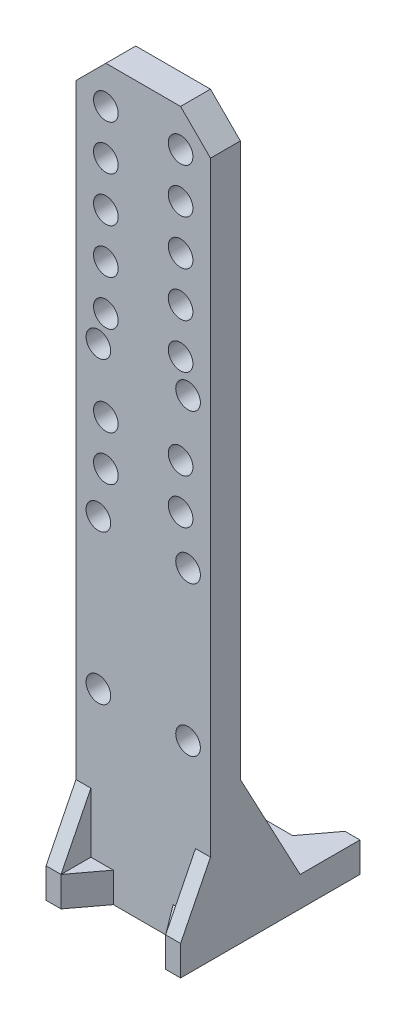
SolidWorks part; units mm, degrees
ref_plane "前视基准面" through (0, 0, 0) normal (0, 0, 1) x (1, 0, 0)
ref_plane "上视基准面" through (0, 0, 0) normal (0, 1, 0) x (1, 0, 0)
ref_plane "右视基准面" through (0, 0, 0) normal (1, 0, 0) x (0, 0, -1)
sketch "草图1" plane through (0, 0, 0) normal (0, 1, 0) x (1, 0, 0)
  line L1 (-9, 8) -> (9, 8)
  line L2 (-9, 8) -> (-9, -8)
  line L3 (-9, -8) -> (9, -8)
  line L4 (9, 8) -> (9, -8)
  line L5 (-9, 8) -> (9, -8) construction
  line L6 (-9, -8) -> (9, 8) construction
  point P0 (0, 0)
  dimension "D1" = 16
  dimension "D2" = 18
extrude "凸台-拉伸1" add sketch "草图1" along normal blind 4
sketch "草图2" plane through (0, 4, 0) normal (0, 1, 0) x (1, 0, 0)
  circle A0 centre (0, 0) radius 1.65
  dimension "D1" = 3.3
extrude "切除-拉伸1" cut sketch "草图2" against normal blind 4
sketch "草图3" plane through (0, 4, 0) normal (0, 1, 0) x (1, 0, 0)
  line L0 (-9, 0) -> (9, 0) construction
  line L1 (-9, 8) -> (-9, -8) construction
  line L2 (9, -8) -> (9, 8) construction
  line L3 (0, 8) -> (0, -8) construction
  line L4 (9, 8) -> (-9, 8) construction
  line L5 (-9, -8) -> (9, -8) construction
  line L6 (-9, -8) -> (-9, -12)
  line L7 (-9, -12) -> (-7, -12)
  line L8 (-7, -12) -> (-4, -8)
  line L9 (-4, -8) -> (-9, -8)
  line L10 (7, -12) -> (4, -8)
  line L11 (9, -12) -> (7, -12)
  line L12 (9, -8) -> (9, -12)
  line L13 (4, -8) -> (9, -8)
  line L14 (9, 12) -> (7, 12)
  line L15 (9, 8) -> (9, 12)
  line L16 (4, 8) -> (9, 8)
  line L17 (7, 12) -> (4, 8)
  line L18 (-7, 12) -> (-4, 8)
  line L19 (-9, 12) -> (-7, 12)
  line L20 (-9, 8) -> (-9, 12)
  line L21 (-4, 8) -> (-9, 8)
  dimension "D1" = 4
  dimension "D2" = 2
  dimension "D3" = 5
extrude "凸台-拉伸2" add sketch "草图3" against normal blind 4
sketch "草图4" plane through (0, 4, 0) normal (0, 1, 0) x (1, 0, 0)
  line L0 (-9, 12) -> (-9, -12) construction
  line L1 (-9, -8) -> (9, -8)
  line L2 (-9, -8) -> (-9, -4)
  line L3 (-9, -4) -> (9, -4)
  line L4 (9, -8) -> (9, -4)
  line L5 (9, -12) -> (9, 12) construction
  dimension "D1" = 4
extrude "凸台-拉伸3" add sketch "草图4" along normal blind 100
sketch "草图5" plane through (9, 0, 0) normal (1, 0, 0) x (0, 0, -1)
  line L0 (-4, 19) -> (-4, 4)
  line L1 (-4, 104) -> (-4, 4) construction
  line L2 (-4, 4) -> (4, 4)
  line L4 (4, 4) -> (-4, 19)
  line L5 (-8, 12) -> (-8, 4)
  line L6 (-8, 104) -> (-8, 4) construction
  line L7 (-8, 4) -> (-12, 4)
  line L8 (-12, 4) -> (-8, 12)
  line L9 (-12, 4) -> (-8, 4) construction
  dimension "D1" = 15
  dimension "D2" = 4
  dimension "D3" = 8
extrude "凸台-拉伸4" add sketch "草图5" against normal blind 2 contours L0 L2 L4 | L8 L5 L7
mirror "镜向1" about plane through (0, 0, 0) normal (1, 0, 0) of "凸台-拉伸4"
sketch "草图6" plane through (0, 0, 4) normal (0, 0, -1) x (-1, 0, 0)
  line L0 (0, 104) -> (0, 4) construction
  line L1 (-9, 104) -> (9, 104) construction
  line L2 (-4, 4) -> (4, 4) construction
  line L3 (-10, 44) -> (10, 44) construction
  line L4 (-9, 104) -> (-9, 19) construction
  line L6 (-7, 19) -> (-9, 19) construction
  circle A0 centre (0, 92) radius 1.65 construction
  circle A1 centre (0, 86) radius 1.65 construction
  circle A2 centre (0, 80) radius 1.65 construction
  circle A3 centre (0, 74) radius 1.65 construction
  circle A4 centre (0, 68) radius 1.65 construction
  circle A5 centre (0, 62) radius 1.65 construction
  circle A6 centre (0, 56) radius 1.65 construction
  circle A7 centre (0, 50) radius 1.65 construction
  circle A8 centre (-6, 44) radius 1.65
  circle A9 centre (6, 44) radius 1.65
  circle A10 centre (6, 64) radius 1.65
  circle A11 centre (-6, 64) radius 1.65
  circle A12 centre (6, 24) radius 1.65
  circle A13 centre (-6, 24) radius 1.65
  circle A14 centre (5, 92) radius 1.65
  circle A15 centre (5, 86) radius 1.65
  circle A16 centre (5, 80) radius 1.65
  circle A17 centre (5, 74) radius 1.65
  circle A18 centre (5, 68) radius 1.65
  circle A20 centre (5, 56) radius 1.65
  circle A21 centre (5, 50) radius 1.65
  circle A22 centre (-5, 50) radius 1.65
  circle A23 centre (-5, 56) radius 1.65
  circle A25 centre (-5, 68) radius 1.65
  circle A26 centre (-5, 74) radius 1.65
  circle A27 centre (-5, 80) radius 1.65
  circle A28 centre (-5, 86) radius 1.65
  circle A29 centre (-5, 92) radius 1.65
  circle A30 centre (5, 62) radius 1.65 [skipped]
  dimension "D2" = 3.3
  dimension "D5" = 3.3
  dimension "D1" = 12
  dimension "D4" = 3
  dimension "D6" = 25
  dimension "D3" = 8
  dimension "D7" = 2
  dimension "D8" = 2
extrude "切除-拉伸2" cut sketch "草图6" against normal blind 10
sketch "草图7" plane through (0, 0, 4) normal (0, 0, -1) x (-1, 0, 0)
  line L0 (9, 104) -> (9, 19) construction
  line L1 (-9, 104) -> (9, 104)
  line L2 (-9, 104) -> (-9, 97)
  line L3 (-9, 97) -> (9, 97)
  line L4 (9, 104) -> (9, 97)
  dimension "D1" = 7
extrude "切除-拉伸3" cut sketch "草图7" against normal blind 10
chamfer "倒角1" distance 4 angle 45 2 edges at (9, 97, 6) (-9, 97, 6)
